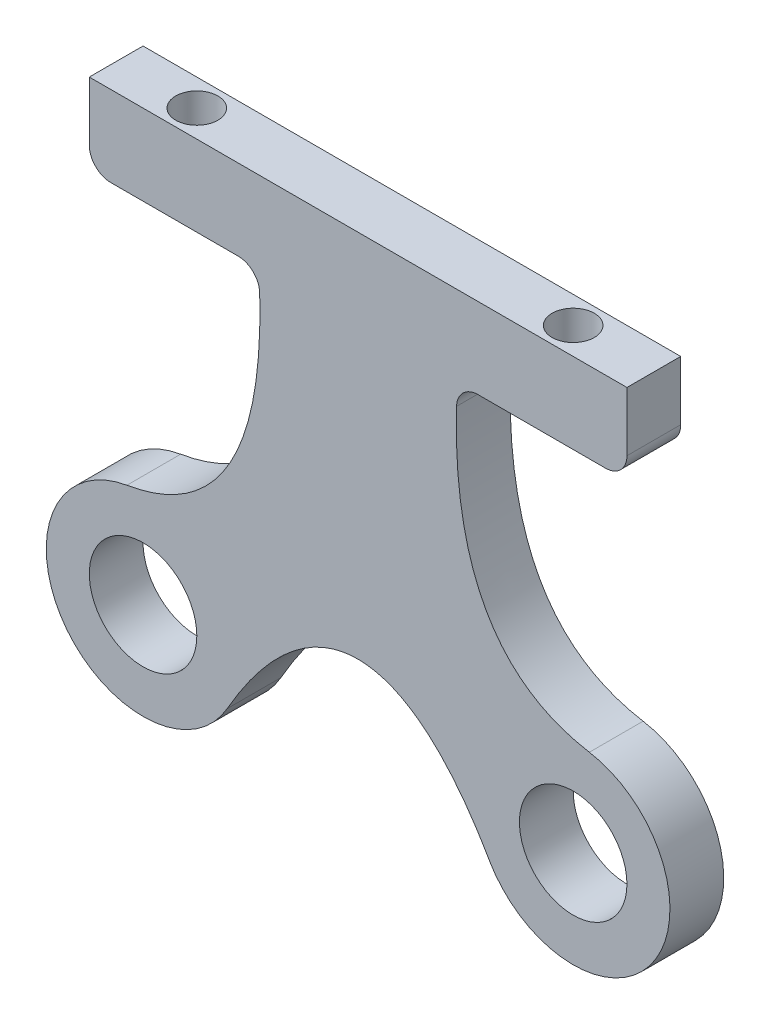
SolidWorks part; units mm, degrees
ref_plane "Front Plane" through (0, 0, 0) normal (0, 0, 1) x (1, 0, 0)
ref_plane "Top Plane" through (0, 0, 0) normal (0, 1, 0) x (1, 0, 0)
ref_plane "Right Plane" through (0, 0, 0) normal (1, 0, 0) x (0, 0, -1)
sketch "Sketch1" plane through (0, 0, 0) normal (0, 0, 1) x (1, 0, 0)
  line L0 (-25.4, -50.8) -> (25.4, -50.8) construction
  line L1 (0, -50.8) -> (0, 0) construction
  line L2 (31.75, 0) -> (-31.75, 0)
  line L3 (-31.75, 0) -> (-31.75, -9.525)
  line L4 (-31.75, -9.525) -> (-11.7361, -9.525)
  line L9 (31.75, -9.525) -> (11.7361, -9.525)
  line L10 (31.75, 0) -> (31.75, -9.525)
  circle A0 centre (-25.4, -50.8) radius 6.35
  circle A1 centre (25.4, -50.8) radius 6.35
  circle A2 centre (-25.4, -50.8) radius 11.43
  circle A3 centre (25.4, -50.8) radius 11.43
  spline S0 degree 3 poles (-15.4784, -56.4752) (-5.0678, -38.2749) (6.3808, -40.5703) (15.4784, -56.4752) knots 0 0 0 0 1 1 1 1
  spline S1 degree 2 poles (-27.3097, -39.5307) (-10.1214, -36.6179) (-11.7361, -9.525) knots 0 0 0 1 1 1
  spline S2 degree 2 poles (27.3097, -39.5307) (10.1214, -36.6179) (11.7361, -9.525) knots 0 0 0 1 1 1
  dimension "D1" = 50.8
  dimension "D3" = 12.7
  dimension "D4" = 5.08
  dimension "D2" = 50.8
  dimension "D5" = 31.75
  dimension "D6" = 9.525
extrude "Boss-Extrude1" add sketch "Sketch1" along normal mid plane 6.35
fillet "Fillet1" radius 2.54 4 edges at (11.7361, -9.525, 0) (-11.7361, -9.525, 0) (31.75, -9.525, 0) (-31.75, -9.525, 0)
hole_wizard "#10 Clearance Hole1" positions "Sketch3" profile "Sketch2" hole size "#10" standard "ANSI Inch"
sketch "Sketch3" plane through (0, -9.525, 0) normal (0, -1, 0) x (-1, 0, 0)
  line L0 (22.225, 0) -> (-22.225, 0) construction
  point P0 (22.225, 0)
  point P2 (-22.225, 0)
  dimension "D1" = 44.45
sketch "Sketch2" plane through (-22.225, -9.525, 0) normal (1, 0, 0) x (0, 0, -1)
  line L0 (0, 0) -> (0, 9.525)
  line L1 (0, 9.525) -> (2.4892, 9.525)
  line L2 (2.4892, 9.525) -> (2.4892, 0)
  line L5 (2.4892, 0) -> (0, 0)
  line L11 (0, -6.35) -> (0, 107.95) construction
  dimension "Thru Hole Dia." = 4.9784
  dimension "Thru Hole Depth" = 9.525
